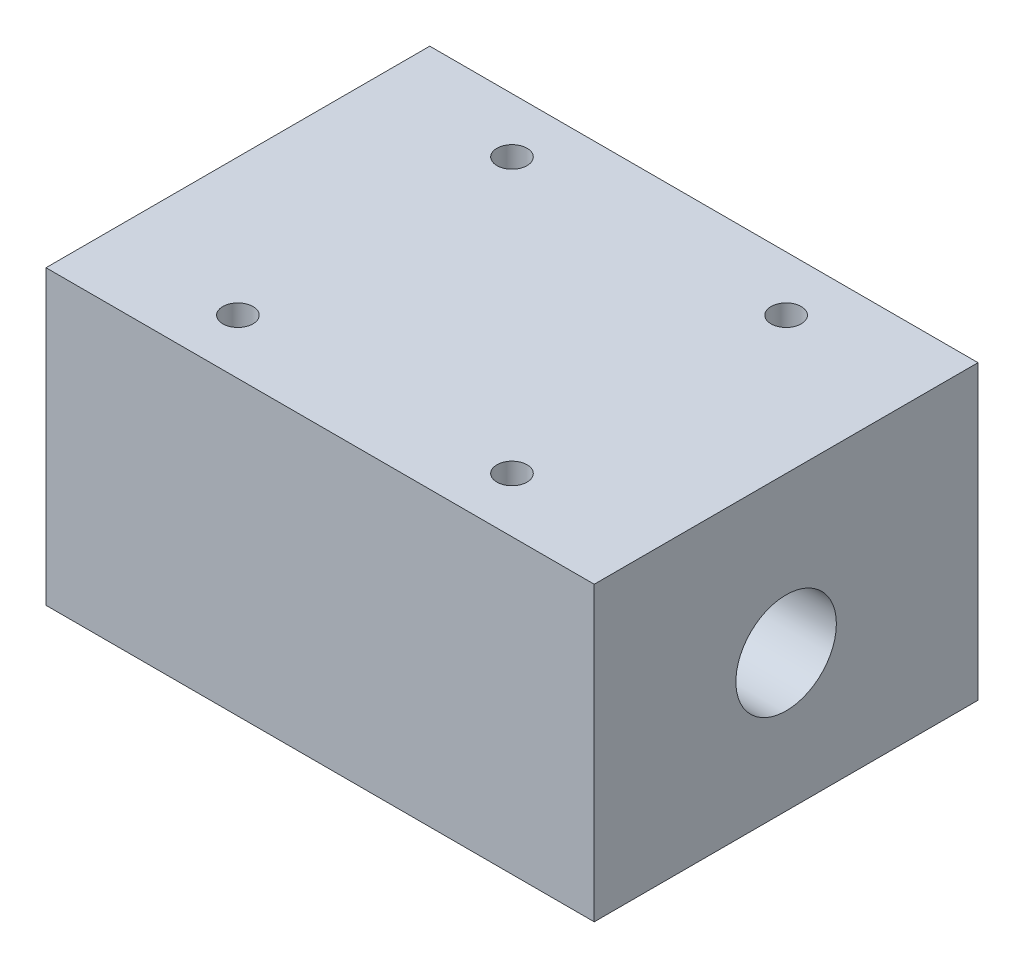
SolidWorks part; units mm, degrees
ref_plane "Front Plane" through (0, 0, 0) normal (0, 0, 1) x (1, 0, 0)
ref_plane "Top Plane" through (0, 0, 0) normal (0, 1, 0) x (1, 0, 0)
ref_plane "Right Plane" through (0, 0, 0) normal (1, 0, 0) x (0, 0, -1)
sketch "Sketch1" plane through (0, 0, 0) normal (0, 1, 0) x (1, 0, 0)
  line L1 (-30, -21) -> (30, -21)
  line L2 (-30, -21) -> (-30, 21)
  line L3 (-30, 21) -> (30, 21)
  line L4 (30, -21) -> (30, 21)
  line L5 (-30, -21) -> (30, 21) construction
  line L6 (-30, 21) -> (30, -21) construction
  point P0 (0, 0)
  dimension "D1" = 60
  dimension "D2" = 42
extrude "Boss-Extrude1" add sketch "Sketch1" along normal blind 32
hole_wizard "M4x0.7 Tapped Hole1" positions "Sketch2" profile "Sketch3" tap size "M4x0.7" standard "ANSI Metric"
sketch "Sketch2" plane through (0, 32, 0) normal (0, 1, 0) x (1, 0, 0)
  line L0 (15, 15) -> (15, -15) construction
  line L1 (30, -21) -> (30, 21) construction
  line L2 (-15, 15) -> (-15, -15) construction
  line L3 (-15, -15) -> (15, -15) construction
  line L4 (15, 15) -> (-15, 15) construction
  line L5 (-15, 0) -> (-30, 0) construction
  line L6 (-30, 21) -> (-30, -21) construction
  point P0 (15, 15)
  point P2 (-15, 15)
  point P4 (-15, -15)
  point P6 (15, -15)
  dimension "D1" = 15
  dimension "D2" = 30
  dimension "D3" = 30
sketch "Sketch3" plane through (15, 32, -15) normal (1, 0, 0) x (0, 0, 1)
  line L0 (0, 0) -> (0, 15.9914)
  line L1 (0, 15.9914) -> (1.65, 15)
  line L2 (1.65, 15) -> (1.65, 0)
  line L5 (1.65, 0) -> (0, 0)
  line L10 (0, 15.9914) -> (-1.65, 15) construction
  line L11 (0, -6.35) -> (0, 107.95) construction
  dimension "Tap Drill Dia." = 3.3
  dimension "Tap Drill Depth" = 15
  dimension "Drill Angle" = 118
cosmetic thread "Hole Thread1" parameters "D1"=8, "D2"=4
cosmetic thread "Hole Thread2" parameters "D1"=8, "D2"=4
cosmetic thread "Hole Thread3" parameters "D1"=8, "D2"=4
cosmetic thread "Hole Thread4" parameters "D1"=8, "D2"=4
sketch "Sketch4" plane through (30, 0, 0) normal (1, 0, 0) x (0, 0, -1)
  line L0 (0, 15) -> (0, 0) construction
  circle A0 centre (0, 15) radius 5.5
  dimension "D2" = 11
  dimension "D1" = 15
extrude "Cut-Extrude1" cut sketch "Sketch4" against normal through all
